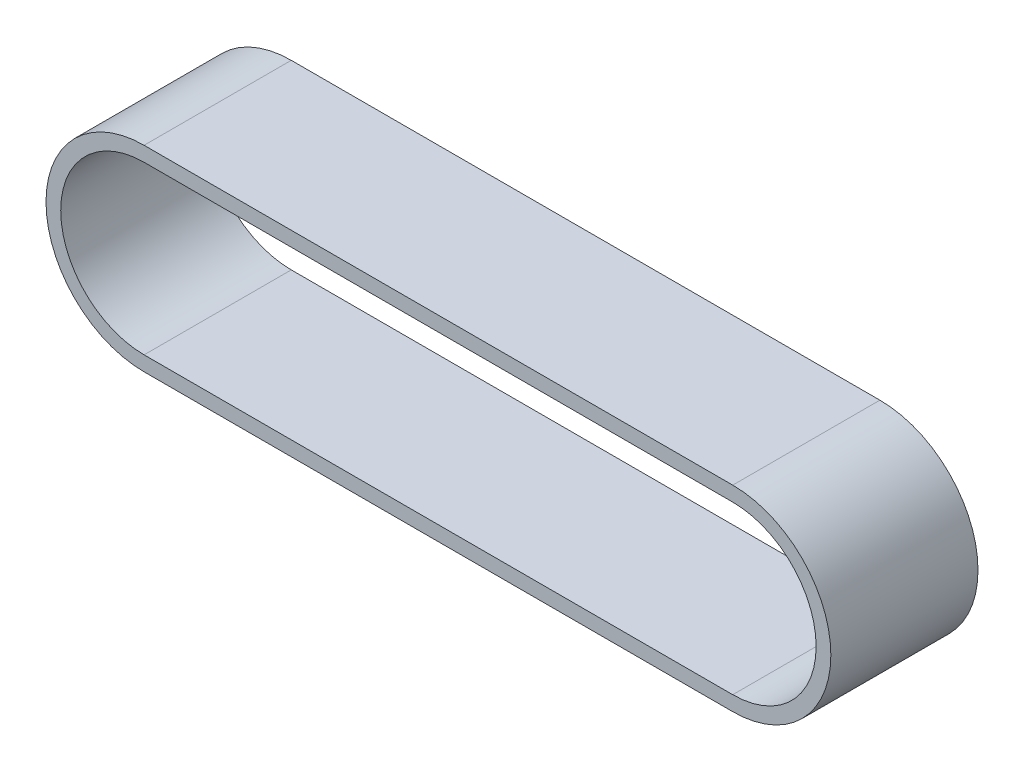
SolidWorks part; units mm, degrees
ref_plane "Front Plane" through (0, 0, 0) normal (0, 0, 1) x (1, 0, 0)
ref_plane "Top Plane" through (0, 0, 0) normal (0, 1, 0) x (1, 0, 0)
ref_plane "Right Plane" through (0, 0, 0) normal (1, 0, 0) x (0, 0, -1)
sketch "Sketch1" plane through (0, 0, 0) normal (0, 0, 1) x (1, 0, 0)
  line L0 (-33.2738, 0) -> (38.5155, 0) construction
  line L1 (0, 38.4016) -> (0, -26.7786) construction
  line L2 (-60, 20) -> (60, 20)
  line L3 (-60, -20) -> (60, -20)
  line L4 (-60, 17) -> (60, 17)
  line L5 (-60, -17) -> (60, -17)
  circle A0 centre (-60, 0) radius 20
  circle A1 centre (-60, 0) radius 17
  circle A2 centre (60, 0) radius 17
  circle A3 centre (60, 0) radius 20
  point P17 (0, -20)
  point P18 (0, -17)
  point P19 (0, 20)
  point P20 (0, 17)
  dimension "D1" = 40
  dimension "D2" = 3
  dimension "D3" = 120
extrude "Boss-Extrude1" add sketch "Sketch1" along normal blind 30 contours A1 L4 A0 L5 | L4 A3 L2 A0 | A3 L4 A2 L5 | L3 A3 L5 A0
